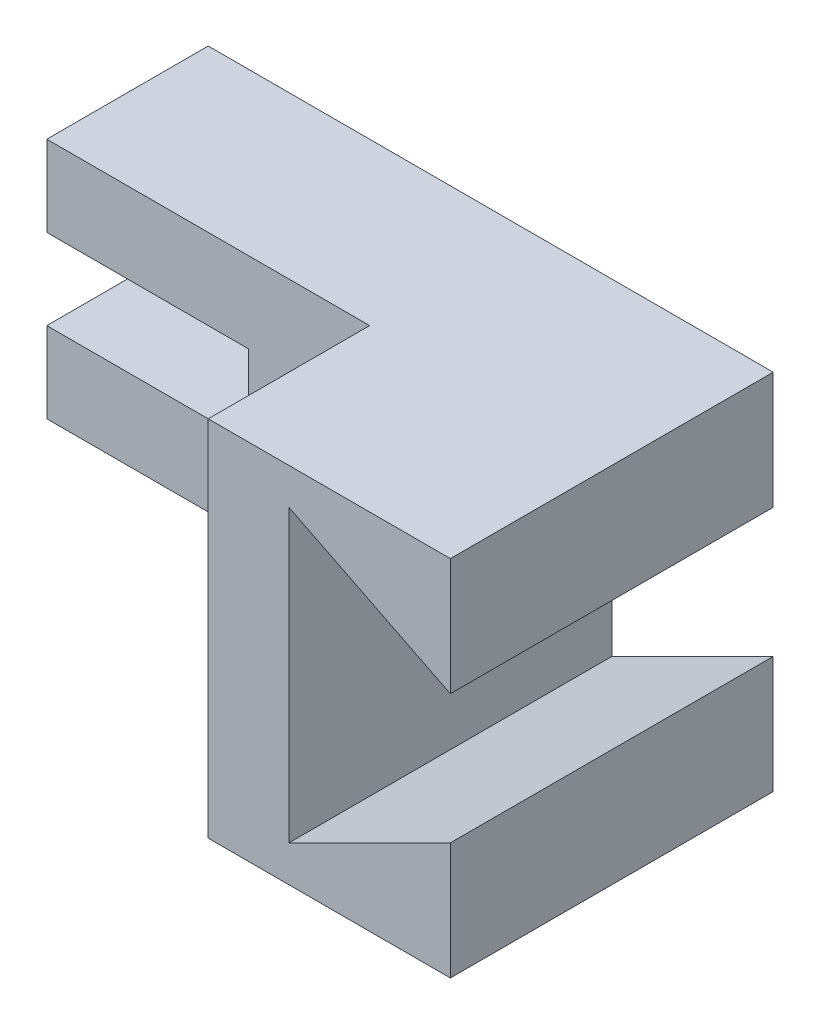
SolidWorks part; units mm, degrees
ref_plane "Ebene vorne" through (0, 0, 0) normal (0, 0, 1) x (1, 0, 0)
ref_plane "Ebene oben" through (0, 0, 0) normal (0, 1, 0) x (1, 0, 0)
ref_plane "Ebene rechts" through (0, 0, 0) normal (1, 0, 0) x (0, 0, -1)
sketch "Skizze1" plane through (0, 0, 0) normal (0, 0, 1) x (1, 0, 0)
  line L0 (0, 0) -> (40, 0)
  line L1 (40, 0) -> (40, 30)
  line L2 (40, 30) -> (0, 30)
  line L3 (0, 30) -> (0, 20)
  line L4 (0, 20) -> (25, 20)
  line L5 (25, 20) -> (25, 10)
  line L6 (25, 10) -> (0, 10)
  line L7 (0, 10) -> (0, 0)
  dimension "D1" = 40
  dimension "D2" = 30
  dimension "D3" = 10
  dimension "D4" = 25
extrude "Aufsatz-Linear austragen1" add sketch "Skizze1" along normal blind 20
sketch "Skizze2" plane through (40, 0, 0) normal (1, 0, 0) x (0, 0, -1)
  line L1 (0, 30) -> (-40, 30)
  line L2 (0, 30) -> (0, -15)
  line L3 (0, -15) -> (-40, -15)
  line L4 (-40, 30) -> (-40, -15)
  dimension "D1" = 45
  dimension "D2" = 40
extrude "Aufsatz-Linear austragen3" add sketch "Skizze2" along normal blind 30
sketch "Skizze3" plane through (0, 0, 40) normal (0, 0, 1) x (1, 0, 0)
  line L0 (70, 15.5) -> (50, 25.5)
  line L1 (70, 30) -> (70, -15) construction
  line L2 (50, 25.5) -> (50, -10.5)
  line L3 (50, -10.5) -> (70, -0.5)
  line L4 (70, 30) -> (40, 30) construction
  dimension "D1" = 36
  dimension "D2" = 4.5
  dimension "D3" = 20
  dimension "D4" = 16
  dimension "D5" = 14.5
extrude "Schnitt-Linear austragen1" cut sketch "Skizze3" against normal blind 40 and the other way through all
